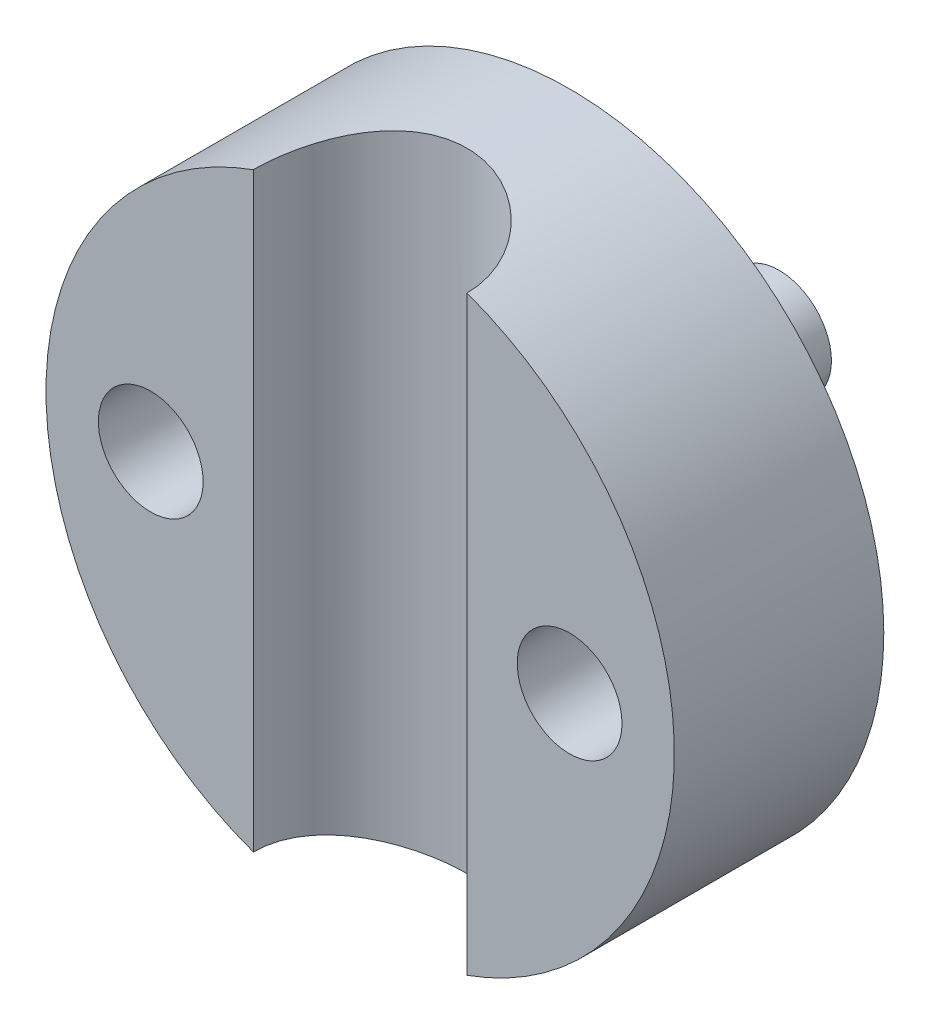
SolidWorks part; units mm, degrees
ref_plane "Front Plane" through (0, 0, 0) normal (0, 0, 1) x (1, 0, 0)
ref_plane "Top Plane" through (0, 0, 0) normal (0, 1, 0) x (1, 0, 0)
ref_plane "Right Plane" through (0, 0, 0) normal (1, 0, 0) x (0, 0, -1)
sketch "Sketch1" plane through (0, 0, 0) normal (0, 0, 1) x (1, 0, 0)
  circle A0 centre (0, 0) radius 19.05
  dimension "D1" = 38.1
extrude "Boss-Extrude1" add sketch "Sketch1" along normal blind 12.7
sketch "Sketch2" plane through (0, 0, 0) normal (0, 0, -1) x (-1, 0, 0)
  circle A0 centre (0, 0) radius 3.175
  dimension "D1" = 6.35
extrude "Boss-Extrude2" add sketch "Sketch2" along normal blind 12.7
sketch "Sketch4" plane through (0, 0, 0) normal (0, 1, 0) x (1, 0, 0)
  line L0 (-19.05, -12.7) -> (19.05, -12.7) construction
  circle A0 centre (0, -12.7) radius 6.477
  dimension "D1" = 12.954
extrude "Cut-Extrude1" cut sketch "Sketch4" along normal through all and the other way through all
sketch "Sketch5" plane through (0, 0, 12.7) normal (0, 0, 1) x (1, 0, 0)
  line L0 (19.05, 0) -> (-19.05, 0) construction
  arc A0 (6.477, -17.9151) -> (6.477, 17.9151) centre (0, 0) ccw construction
  arc A1 (-6.477, 17.9151) -> (-6.477, -17.9151) centre (0, 0) ccw construction
  circle A2 centre (12.7, 0) radius 3.175
  circle A3 centre (-12.7, 0) radius 3.175
  dimension "D1" = 6.35
  dimension "D3" = 6.35
  dimension "D2" = 6.35
  dimension "D4" = 6.35
extrude "Cut-Extrude2" cut sketch "Sketch5" against normal blind 73.66
